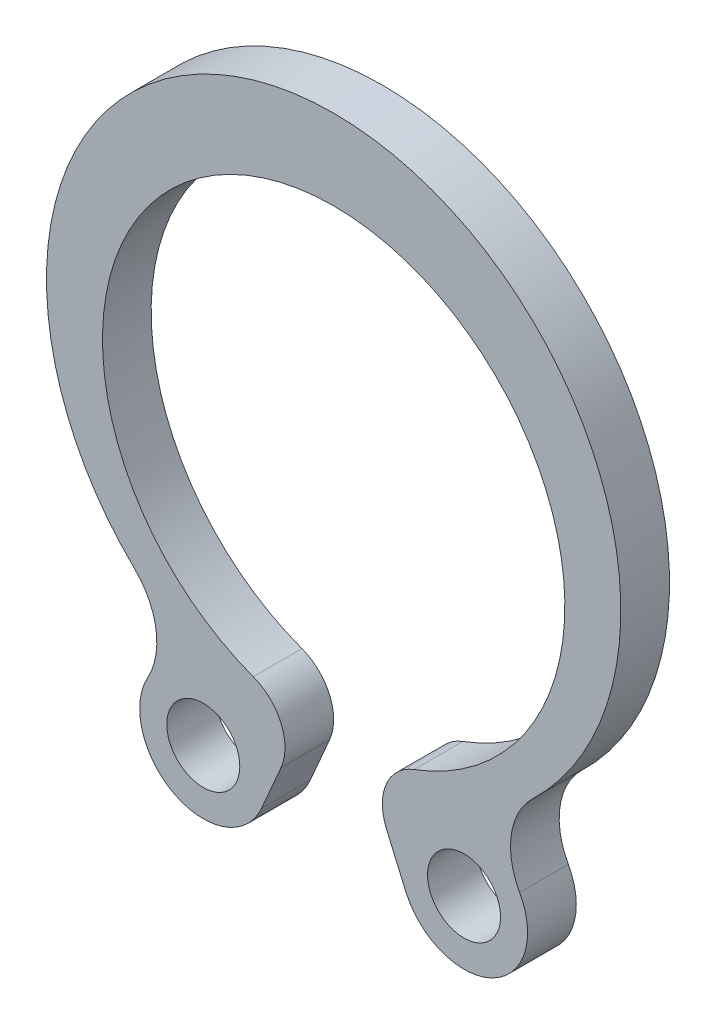
SolidWorks part; units mm, degrees
ref_plane "Спереди" through (0, 0, 0) normal (0, 0, 1) x (1, 0, 0)
ref_plane "Сверху" through (0, 0, 0) normal (0, 1, 0) x (1, 0, 0)
ref_plane "Справа" through (0, 0, 0) normal (1, 0, 0) x (0, 0, -1)
sketch "Clipboard" plane through (0, 0, 0) normal (0, 0, 1) x (1, 0, 0)
  circle A0 centre (0, 0) radius 5
  dimension "D1" = 10
sketch "Sketch1" plane through (0, 0, 0) normal (0, 0, 1) x (1, 0, 0)
  line L0 (0, -8.8044) -> (0, 8.5575) construction
  line L1 (0, 0) -> (-2.6788, -6.1894) construction
  line L2 (-2.6788, -6.1894) -> (-3.3671, -5.8915) construction
  line L3 (0, 0) -> (2.6788, -6.1894) construction
  line L4 (1.0823, -5.7882) -> (1.4804, -6.708)
  line L5 (-1.4804, -6.708) -> (-1.0823, -5.7882)
  arc A0 (-4.0928, -3.7496) -> (4.0928, -3.7496) centre (0, 0.5) cw
  arc A2 (-3.8211, -5.5567) -> (-1.4804, -6.708) centre (-2.6788, -6.1894) ccw
  arc A3 (-3.8211, -5.5567) -> (-4.0928, -3.7496) centre (-5.1333, -4.83) ccw
  arc A4 (-1.6522, -4.4534) -> (-1.0823, -5.7882) centre (-2, -5.391) cw
  circle A5 centre (-2.6788, -6.1894) radius 0.75
  circle A6 centre (2.6788, -6.1894) radius 0.75
  arc A7 (1.6522, -4.4534) -> (1.0823, -5.7882) centre (2, -5.391) ccw
  arc A8 (3.8211, -5.5567) -> (4.0928, -3.7496) centre (5.1333, -4.83) cw
  arc A9 (3.8211, -5.5567) -> (1.4804, -6.708) centre (2.6788, -6.1894) cw
  arc A11 (1.6522, -4.4534) -> (-1.6522, -4.4534) centre (0, 0) ccw
  dimension "D2" = 9.5
  dimension "D3" = 11.8
  dimension "D4" = 1.5
  dimension "R1" = 1.5
  dimension "R2" = 1
  dimension "a" = 3.3
  dimension "L" = 2
  dimension "e" = 0.5
extrude "Body" add sketch "Sketch1" along normal blind 1
